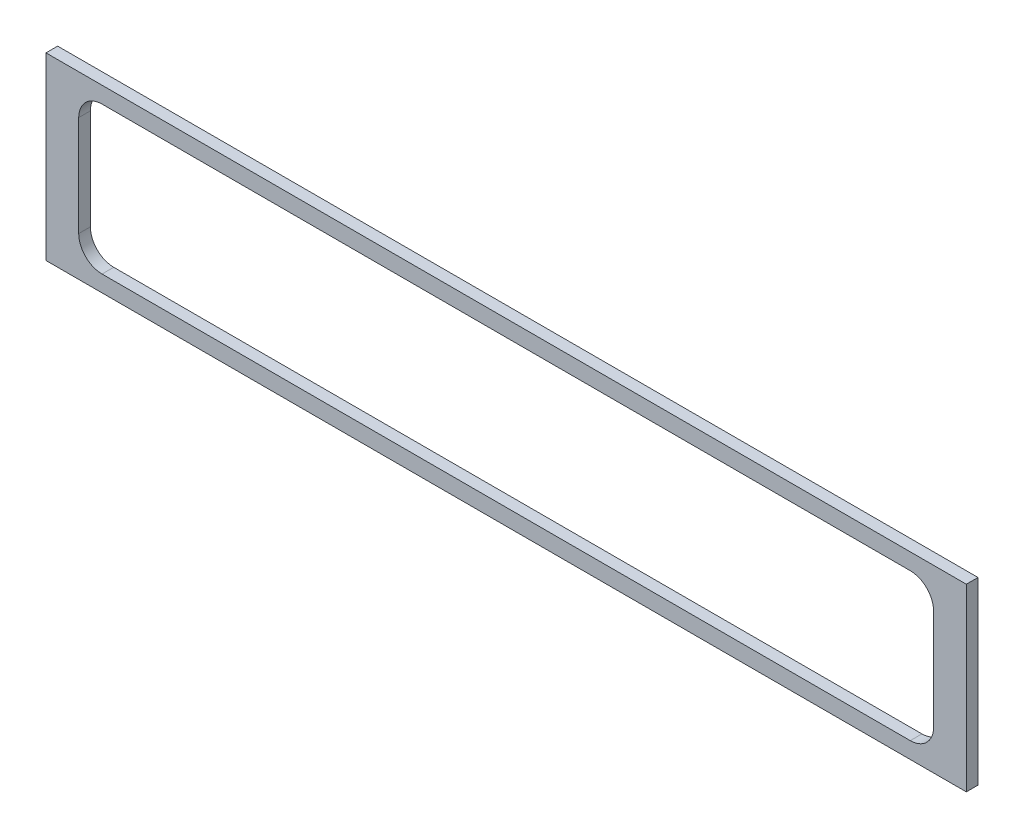
SolidWorks part; units mm, degrees
ref_plane "Płaszczyzna przednia" through (0, 0, 0) normal (0, 0, 1) x (1, 0, 0)
ref_plane "Płaszczyzna górna" through (0, 0, 0) normal (0, 1, 0) x (1, 0, 0)
ref_plane "Płaszczyzna prawa" through (0, 0, 0) normal (1, 0, 0) x (0, 0, -1)
sketch "Szkic1" plane through (0, 0, 0) normal (0, 0, 1) x (1, 0, 0)
  line L1 (-279.6047, -32.773) -> (114.3953, -32.773)
  line L2 (-279.6047, -32.773) -> (-279.6047, -109.773)
  line L3 (-279.6047, -109.773) -> (114.3953, -109.773)
  line L4 (114.3953, -32.773) -> (114.3953, -109.773)
  dimension "D1" = 394
  dimension "D2" = 77
extrude "Dodanie-wyciągnięcie1" add sketch "Szkic1" along normal blind 5
sketch "Szkic2" plane through (0, 0, 5) normal (0, 0, 1) x (1, 0, 0)
  line L0 (-255.6047, -39.773) -> (90.3953, -39.773)
  line L1 (114.3953, -32.773) -> (-279.6047, -32.773) construction
  line L2 (-255.6047, -102.773) -> (90.3953, -102.773)
  line L3 (-279.6047, -109.773) -> (114.3953, -109.773) construction
  line L4 (100.3953, -49.773) -> (100.3953, -92.773)
  line L5 (114.3953, -109.773) -> (114.3953, -32.773) construction
  line L6 (-265.6047, -49.773) -> (-265.6047, -92.773)
  line L7 (-279.6047, -32.773) -> (-279.6047, -109.773) construction
  arc A0 (90.3953, -39.773) -> (100.3953, -49.773) centre (90.3953, -49.773) cw
  arc A1 (100.3953, -92.773) -> (90.3953, -102.773) centre (90.3953, -92.773) cw
  arc A2 (-255.6047, -102.773) -> (-265.6047, -92.773) centre (-255.6047, -92.773) cw
  arc A3 (-265.6047, -49.773) -> (-255.6047, -39.773) centre (-255.6047, -49.773) cw
  dimension "D5" = 10
  dimension "D1" = 7
  dimension "D2" = 7
  dimension "D3" = 14
  dimension "D4" = 14
extrude "Wytnij-wyciągnięcie1" cut sketch "Szkic2" against normal blind 10
